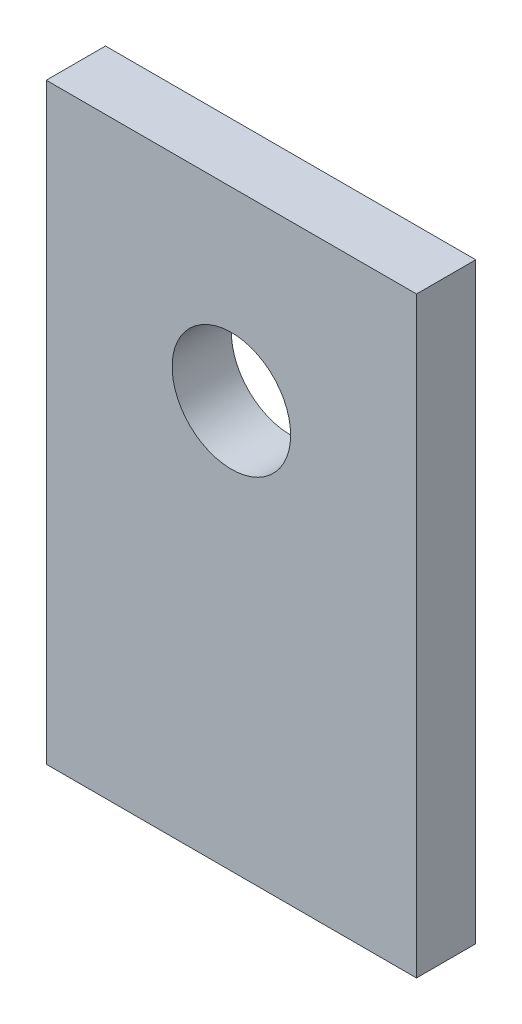
SolidWorks part; units mm, degrees
ref_plane "Front Plane" through (0, 0, 0) normal (0, 0, 1) x (1, 0, 0)
ref_plane "Top Plane" through (0, 0, 0) normal (0, 1, 0) x (1, 0, 0)
ref_plane "Right Plane" through (0, 0, 0) normal (1, 0, 0) x (0, 0, -1)
sketch "Sketch3" plane through (0, 0, 0) normal (0, 0, 1) x (1, 0, 0)
  line L1 (-12.5, 20) -> (12.5, 20)
  line L2 (-12.5, 20) -> (-12.5, -20)
  line L3 (-12.5, -20) -> (12.5, -20)
  line L4 (12.5, 20) -> (12.5, -20)
  line L5 (-12.5, 20) -> (12.5, -20) construction
  line L6 (-12.5, -20) -> (12.5, 20) construction
  circle A1 centre (0, 7.5) radius 4
  point P0 (0, 0)
  dimension "D3" = 8
  dimension "D1" = 25
  dimension "D2" = 40
  dimension "D4" = 12.5
  dimension "D5" = 12.5
extrude "Boss-Extrude1" add sketch "Sketch3" along normal blind 4
